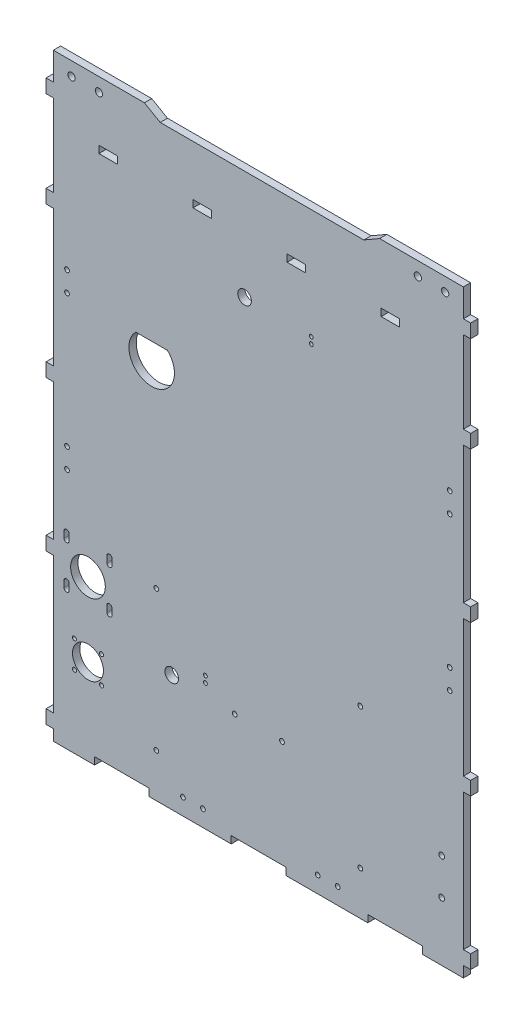
SolidWorks part; units mm, degrees
material "PMMA"
ref_plane "Plan de face" through (0, 0, 0) normal (0, 0, 1) x (1, 0, 0)
ref_plane "Plan de dessus" through (0, 0, 0) normal (0, 1, 0) x (1, 0, 0)
ref_plane "Plan de droite" through (0, 0, 0) normal (1, 0, 0) x (0, 0, -1)
sketch "Esquisse2" plane through (0, 0, -12) normal (0, 0, 1) x (1, 0, 0)
  line L1 (458.3, -56) -> (0, -56)
  line L2 (458.3, -56) -> (458.3, 601.3433)
  line L3 (458.3, 601.3433) -> (0, 601.3433)
  line L4 (-8, -44) -> (-8, -29)
  line L5 (-8, 121) -> (-8, 136)
  line L6 (458.3, -65.2452) -> (450.3, -65.2452) construction
  line L7 (450.3, -21) -> (450.3, -15.3297) construction
  line L8 (-8, 601.3433) -> (0, 601.3433) construction
  line L9 (-8, 286) -> (-8, 301)
  line L10 (0, -56) -> (0, -44)
  line L11 (0, 194.5096) -> (0, 601.3433) construction
  line L12 (0, -44) -> (-8, -44)
  line L13 (-8, -44) -> (-8, -29)
  line L14 (-8, -29) -> (0, -29)
  line L15 (0, -29) -> (0, 121)
  line L16 (0, 121) -> (-8, 121)
  line L17 (-8, 121) -> (-8, 136)
  line L18 (-8, 136) -> (0, 136)
  line L19 (0, 136) -> (0, 286)
  line L20 (0, 286) -> (-8, 286)
  line L21 (-8, 286) -> (-8, 301)
  line L22 (-8, 301) -> (0, 301)
  line L23 (0, 301) -> (0, 451)
  line L24 (0, 451) -> (-8, 451)
  line L25 (-8, 451) -> (-8, 466)
  line L26 (-8, 466) -> (0, 466)
  line L27 (0, 466) -> (0, 556)
  line L28 (0, 556) -> (-8, 556)
  line L29 (-8, 556) -> (-8, 571)
  line L30 (-8, 571) -> (0, 571)
  line L32 (-8, 451) -> (-8, 466)
  line L34 (-8, 556) -> (-8, 571)
  line L35 (0, 571) -> (0, 601.3433)
  arc A0 (55, 38.5) -> (21, 38.5) centre (38, 38.5) ccw construction
  arc A1 (21, 38.5) -> (55, 38.5) centre (38, 38.5) ccw construction
  arc A2 (25.4008, 53.3492) -> (20.9008, 53.3492) centre (23.1508, 53.3492) ccw construction
  arc A3 (20.9008, 53.3492) -> (25.4008, 53.3492) centre (23.1508, 53.3492) ccw construction
  arc A4 (25.4008, 23.6508) -> (20.9008, 23.6508) centre (23.1508, 23.6508) ccw construction
  arc A5 (20.9008, 23.6508) -> (25.4008, 23.6508) centre (23.1508, 23.6508) ccw construction
  arc A6 (55.0992, 53.3492) -> (50.5992, 53.3492) centre (52.8492, 53.3492) ccw construction
  arc A7 (50.5992, 53.3492) -> (55.0992, 53.3492) centre (52.8492, 53.3492) ccw construction
  arc A8 (55.0992, 23.6508) -> (50.5992, 23.6508) centre (52.8492, 23.6508) ccw construction
  arc A9 (50.5992, 23.6508) -> (55.0992, 23.6508) centre (52.8492, 23.6508) ccw construction
  arc A10 (55, 38.5) -> (21, 38.5) centre (38, 38.5) ccw
  arc A11 (21, 38.5) -> (55, 38.5) centre (38, 38.5) ccw
  arc A12 (25.4008, 53.3492) -> (20.9008, 53.3492) centre (23.1508, 53.3492) ccw
  arc A13 (20.9008, 53.3492) -> (25.4008, 53.3492) centre (23.1508, 53.3492) ccw
  arc A14 (25.4008, 23.6508) -> (20.9008, 23.6508) centre (23.1508, 23.6508) ccw
  arc A15 (20.9008, 23.6508) -> (25.4008, 23.6508) centre (23.1508, 23.6508) ccw
  arc A16 (55.0992, 53.3492) -> (50.5992, 53.3492) centre (52.8492, 53.3492) ccw
  arc A17 (50.5992, 53.3492) -> (55.0992, 53.3492) centre (52.8492, 53.3492) ccw
  arc A18 (55.0992, 23.6508) -> (50.5992, 23.6508) centre (52.8492, 23.6508) ccw
  arc A19 (50.5992, 23.6508) -> (55.0992, 23.6508) centre (52.8492, 23.6508) ccw
  point P68 (-4, 556)
  dimension "D1" = 8
  dimension "D2" = 15
  dimension "D3" = 15
  dimension "D4" = 15
  dimension "D5" = 15
  dimension "D6" = 15
  dimension "D7" = 9.2452
  dimension "D8" = 12
  dimension "D9" = 150
  dimension "D10" = 150
  dimension "D11" = 150
  dimension "D12" = 90
  dimension "D13" = 8
extrude "Boss.-Extru.1" add sketch "Esquisse2" along normal blind 8
sketch "Esquisse3" plane through (0, 0, -4) normal (0, 0, 1) x (1, 0, 0)
  line L0 (458.3, 528) -> (0, 528) construction
  line L1 (458.3, -56) -> (458.3, 601.3433) construction
  line L2 (0, 194.5096) -> (0, 601.3433) construction
  line L3 (458.3, 601.3433) -> (0, 601.3433) construction
  line L4 (0, 536) -> (458.3, 536) construction
  line L5 (153.3333, 528) -> (173.6333, 528)
  line L6 (50, 536) -> (70.3, 536)
  line L7 (50, 536) -> (50, 528)
  line L8 (50, 528) -> (70.3, 528)
  line L9 (70.3, 536) -> (70.3, 528)
  line L10 (153.3333, 536) -> (173.6333, 536)
  line L11 (173.6333, 536) -> (173.6333, 528)
  line L12 (153.3333, 536) -> (153.3333, 528)
  line L13 (256.6667, 528) -> (276.9667, 528)
  line L14 (256.6667, 536) -> (276.9667, 536)
  line L15 (276.9667, 536) -> (276.9667, 528)
  line L16 (256.6667, 536) -> (256.6667, 528)
  line L17 (360, 528) -> (380.3, 528)
  line L18 (360, 536) -> (380.3, 536)
  line L19 (380.3, 536) -> (380.3, 528)
  line L20 (360, 536) -> (360, 528)
  dimension "D1" = 8
  dimension "D2" = 20.3
  dimension "D3" = 50
  dimension "D5" = 65.3433
  dimension "D6" = 78
  dimension "D4" = 4
extrude "Enlèv. mat.-Extru.1" cut sketch "Esquisse3" against normal blind 8
sketch "Esquisse4" plane through (0, 0, -4) normal (0, 0, 1) x (1, 0, 0)
  line L0 (229.15, 640.3) -> (229.15, -56) construction
  line L1 (358.3, 601.3433) -> (340.9795, 591.3433)
  line L2 (340.9795, 591.3433) -> (117.3205, 591.3433)
  line L3 (458.3, -56) -> (458.3, 601.3433) construction
  line L4 (100, 601.3433) -> (117.3205, 591.3433)
  line L5 (0, 571) -> (0, 601.3433) construction
  line L24 (0, 601.3433) -> (0, 571)
  line L25 (0, 571) -> (-8, 571)
  line L26 (-8, 571) -> (-8, 556)
  line L27 (-8, 556) -> (0, 556)
  line L28 (0, 556) -> (0, 466)
  line L29 (0, 466) -> (-8, 466)
  line L30 (-8, 466) -> (-8, 451)
  line L31 (-8, 451) -> (0, 451)
  line L32 (0, 451) -> (0, 301)
  line L33 (0, 301) -> (-8, 301)
  line L34 (-8, 301) -> (-8, 286)
  line L35 (-8, 286) -> (0, 286)
  line L36 (0, 286) -> (0, 136)
  line L37 (0, 136) -> (-8, 136)
  line L38 (-8, 136) -> (-8, 121)
  line L39 (-8, 121) -> (0, 121)
  line L40 (0, 121) -> (0, -29)
  line L41 (0, -29) -> (-8, -29)
  line L42 (-8, -29) -> (-8, -44)
  line L43 (-8, -44) -> (0, -44)
  line L44 (0, -44) -> (0, -56)
  line L45 (0, -56) -> (458.3, -56)
  line L46 (458.3, -56) -> (458.3, 601.3433)
  line L47 (458.3, 601.3433) -> (0, 601.3433)
  line L69 (0, -56) -> (229.15, -56)
  line L71 (358.3, 601.3433) -> (100, 601.3433)
  point P14 (229.15, 591.3433)
  dimension "D2" = 30
  dimension "D3" = 20
  dimension "D4" = 100
  dimension "D5" = 100
  dimension "D1" = 0
extrude "Enlèv. mat.-Extru.2" cut sketch "Esquisse4" against normal blind 10 contours L71 L4 L2 L1
sketch "Esquisse5" plane through (0, 0, -4) normal (0, 0, 1) x (1, 0, 0)
  line L1 (340.9795, 591.3433) -> (117.3205, 591.3433) construction
  line L2 (458.3, -56) -> (0, -56) construction
  line L4 (225.15, 591.3433) -> (225.15, -56) construction
  line L5 (450.3, -44) -> (450.3, -56)
  line L6 (458.3, -44) -> (450.3, -44)
  line L7 (458.3, -56) -> (450.3, -56)
  line L8 (450.3, -29) -> (458.3, -29)
  line L9 (450.3, 121) -> (450.3, -29)
  line L10 (458.3, 121) -> (450.3, 121)
  line L11 (229.15, -56) -> (0, -56)
  line L12 (450.3, 136) -> (458.3, 136)
  line L13 (450.3, 286) -> (450.3, 136)
  line L14 (458.3, 286) -> (450.3, 286)
  line L16 (450.3, 301) -> (458.3, 301)
  line L17 (450.3, 451) -> (450.3, 301)
  line L18 (458.3, 451) -> (450.3, 451)
  line L20 (450.3, 466) -> (458.3, 466)
  line L21 (450.3, 556) -> (450.3, 466)
  line L22 (458.3, 556) -> (450.3, 556)
  line L24 (450.3, 571) -> (458.3, 571)
  line L25 (450.3, 601.3433) -> (450.3, 571)
  line L26 (458.3, -56) -> (458.3, 601.3433) construction
  line L27 (458.3, 601.3433) -> (358.3, 601.3433) construction
  line L28 (458.3, 601.3433) -> (358.3, 601.3433)
  line L29 (358.3, 601.3433) -> (340.9795, 591.3433)
  line L30 (340.9795, 591.3433) -> (117.3205, 591.3433)
  line L31 (117.3205, 591.3433) -> (100, 601.3433)
  line L32 (100, 601.3433) -> (0, 601.3433)
  line L33 (0, 601.3433) -> (0, 571)
  line L34 (0, 571) -> (-8, 571)
  line L35 (-8, 571) -> (-8, 556)
  line L36 (-8, 556) -> (0, 556)
  line L37 (0, 556) -> (0, 466)
  line L38 (0, 466) -> (-8, 466)
  line L39 (-8, 466) -> (-8, 451)
  line L40 (-8, 451) -> (0, 451)
  line L41 (0, 451) -> (0, 301)
  line L42 (0, 301) -> (-8, 301)
  line L43 (-8, 301) -> (-8, 286)
  line L44 (-8, 286) -> (0, 286)
  line L45 (0, 286) -> (0, 136)
  line L46 (0, 136) -> (-8, 136)
  line L47 (-8, 136) -> (-8, 121)
  line L48 (-8, 121) -> (0, 121)
  line L49 (0, 121) -> (0, -29)
  line L50 (0, -29) -> (-8, -29)
  line L51 (-8, -29) -> (-8, -44)
  line L52 (-8, -44) -> (0, -44)
  line L53 (0, -44) -> (0, -56)
  line L54 (0, -56) -> (458.3, -56)
  line L55 (458.3, -56) -> (458.3, 601.3433)
  line L61 (0, 601.3433) -> (0, 571) construction
  line L62 (0, 571) -> (-8, 571) construction
  line L63 (-8, 571) -> (-8, 556) construction
  line L64 (-8, 556) -> (0, 556) construction
  line L65 (0, 556) -> (0, 466) construction
  line L66 (0, 466) -> (-8, 466) construction
  line L67 (-8, 466) -> (-8, 451) construction
  line L68 (-8, 451) -> (0, 451) construction
  line L69 (0, 451) -> (0, 301) construction
  line L70 (0, 301) -> (-8, 301) construction
  line L71 (-8, 301) -> (-8, 286) construction
  line L72 (-8, 286) -> (0, 286) construction
  line L73 (0, 286) -> (0, 136) construction
  line L74 (0, 136) -> (-8, 136) construction
  line L75 (-8, 136) -> (-8, 121) construction
  line L76 (-8, 121) -> (0, 121) construction
  line L77 (0, 121) -> (0, -29) construction
  line L78 (0, -29) -> (-8, -29) construction
  line L79 (-8, -29) -> (-8, -44) construction
  line L80 (-8, -44) -> (0, -44) construction
  line L81 (0, -44) -> (0, -56) construction
  line L82 (458.3, -56) -> (458.3, 601.3433)
  line L83 (458.3, 601.3433) -> (450.3, 601.3433)
  dimension "D2" = 225.15
  dimension "D1" = 0
extrude "Enlèv. mat.-Extru.3" cut sketch "Esquisse5" against normal blind 10 and the other way through all contours L8 L82 L10 L9 | L7 L82 L6 L5 | L12 L82 L14 L13 | L16 L82 L18 L17 | L20 L82 L22 L21 | L82 L83 L25 L24
sketch "Esquisse6" plane through (0, 0, -12) normal (0, 0, 1) x (1, 0, 0)
  line L4 (17, 53.8297) -> (17, 23.1703)
  line L5 (22.6703, 17.5) -> (53.3297, 17.5)
  line L6 (59, 23.1703) -> (59, 53.8297)
  line L7 (53.3297, 59.5) -> (22.6703, 59.5)
  line L8 (17, 53.8297) -> (17, 23.1703)
  line L9 (22.6703, 17.5) -> (53.3297, 17.5)
  line L10 (59, 23.1703) -> (59, 53.8297)
  line L11 (53.3297, 59.5) -> (22.6703, 59.5)
  arc A0 (55, 38.5) -> (21, 38.5) centre (38, 38.5) ccw construction
  arc A1 (21, 38.5) -> (55, 38.5) centre (38, 38.5) ccw construction
  arc A2 (25.4008, 53.3492) -> (20.9008, 53.3492) centre (23.1508, 53.3492) ccw construction
  arc A3 (20.9008, 53.3492) -> (25.4008, 53.3492) centre (23.1508, 53.3492) ccw construction
  arc A4 (22.6703, 59.5) -> (17, 53.8297) centre (38, 38.5) ccw
  arc A5 (17, 23.1703) -> (22.6703, 17.5) centre (38, 38.5) ccw
  arc A6 (53.3297, 17.5) -> (59, 23.1703) centre (38, 38.5) ccw
  arc A7 (59, 53.8297) -> (53.3297, 59.5) centre (38, 38.5) ccw
  arc A8 (22.6703, 59.5) -> (17, 53.8297) centre (38, 38.5) ccw
  arc A9 (17, 23.1703) -> (22.6703, 17.5) centre (38, 38.5) ccw
  arc A10 (53.3297, 17.5) -> (59, 23.1703) centre (38, 38.5) ccw
  arc A11 (59, 53.8297) -> (53.3297, 59.5) centre (38, 38.5) ccw
  arc A12 (50.5992, 53.3492) -> (55.0992, 53.3492) centre (52.8492, 53.3492) ccw construction
  arc A13 (55.0992, 53.3492) -> (50.5992, 53.3492) centre (52.8492, 53.3492) ccw construction
  arc A14 (55.0992, 23.6508) -> (50.5992, 23.6508) centre (52.8492, 23.6508) ccw construction
  arc A15 (50.5992, 23.6508) -> (55.0992, 23.6508) centre (52.8492, 23.6508) ccw construction
  arc A16 (25.4008, 23.6508) -> (20.9008, 23.6508) centre (23.1508, 23.6508) ccw construction
  arc A17 (20.9008, 23.6508) -> (25.4008, 23.6508) centre (23.1508, 23.6508) ccw construction
  arc A18 (55, 38.5) -> (21, 38.5) centre (38, 38.5) ccw
  arc A19 (21, 38.5) -> (55, 38.5) centre (38, 38.5) ccw
  arc A20 (25.4008, 53.3492) -> (20.9008, 53.3492) centre (23.1508, 53.3492) ccw
  arc A21 (20.9008, 53.3492) -> (25.4008, 53.3492) centre (23.1508, 53.3492) ccw
  arc A22 (50.5992, 53.3492) -> (55.0992, 53.3492) centre (52.8492, 53.3492) ccw
  arc A23 (55.0992, 53.3492) -> (50.5992, 53.3492) centre (52.8492, 53.3492) ccw
  arc A24 (55.0992, 23.6508) -> (50.5992, 23.6508) centre (52.8492, 23.6508) ccw
  arc A25 (50.5992, 23.6508) -> (55.0992, 23.6508) centre (52.8492, 23.6508) ccw
  arc A26 (25.4008, 23.6508) -> (20.9008, 23.6508) centre (23.1508, 23.6508) ccw
  arc A27 (20.9008, 23.6508) -> (25.4008, 23.6508) centre (23.1508, 23.6508) ccw
  dimension "D1" = 0
extrude "Boss.-Extru.2" add sketch "Esquisse6" along normal blind 8
sketch "Esquisse7" plane through (0, 0, -4) normal (0, 0, 1) x (1, 0, 0)
  line L0 (38, 38.5) -> (38, 119.5) construction
  circle A0 centre (38, 119.5) radius 19.05
  dimension "D2" = 38.1
  dimension "D1" = 81
extrude "Enlèv. mat.-Extru.4" cut sketch "Esquisse7" against normal blind 10
sketch "Esquisse8" plane through (0, 0, -4) normal (0, 0, 1) x (1, 0, 0)
  circle A0 centre (61.55, 143.05) radius 2.8 construction
  circle A1 centre (14.45, 143.05) radius 2.8 construction
  circle A2 centre (14.45, 95.95) radius 2.8 construction
  circle A3 centre (61.55, 95.95) radius 2.8 construction
  circle A4 centre (61.55, 143.05) radius 2.8
  circle A5 centre (14.45, 143.05) radius 2.8
  circle A6 centre (14.45, 95.95) radius 2.8
  circle A7 centre (61.55, 95.95) radius 2.8
extrude "Enlèv. mat.-Extru.5" cut sketch "Esquisse8" against normal blind 10
sketch "Esquisse9" plane through (0, 0, -4) normal (0, 0, 1) x (1, 0, 0)
  circle A0 centre (426.5, 48.5) radius 3.15 construction
  circle A1 centre (426.5, 8.5) radius 3.15 construction
  circle A2 centre (426.5, 48.5) radius 3.15
  circle A3 centre (426.5, 8.5) radius 3.15
extrude "Enlèv. mat.-Extru.6" cut sketch "Esquisse9" against normal blind 10
sketch "Esquisse10" plane through (0, 0, -4) normal (0, 0, 1) x (1, 0, 0)
  circle A0 centre (251.15, 69.5) radius 2.65 construction
  circle A1 centre (199.15, 69.5) radius 2.65 construction
  circle A2 centre (251.15, 69.5) radius 2.65
  circle A3 centre (199.15, 69.5) radius 2.65
extrude "Enlèv. mat.-Extru.7" cut sketch "Esquisse10" against normal blind 10
sketch "Esquisse12" plane through (0, 0, -12) normal (0, 0, -1) x (-1, 0, 0)
  line L0 (-450.3, -56) -> (0, -56) construction
  line L1 (-405.3, -56) -> (-345.3, -56)
  line L2 (-405.3, -56) -> (-405.3, -48)
  line L3 (-405.3, -48) -> (-345.3, -48)
  line L4 (-345.3, -56) -> (-345.3, -48)
  line L5 (-255.3, -56) -> (-195.3, -56)
  line L6 (-255.3, -56) -> (-255.3, -48)
  line L7 (-255.3, -48) -> (-195.3, -48)
  line L8 (-195.3, -56) -> (-195.3, -48)
  line L9 (-255.3, -48) -> (-255.3, -56) construction
  line L10 (-105.3, -56) -> (-45.3, -56)
  line L11 (-105.3, -56) -> (-105.3, -48)
  line L12 (-105.3, -48) -> (-45.3, -48)
  line L13 (-45.3, -56) -> (-45.3, -48)
  line L14 (-105.3, -48) -> (-105.3, -56) construction
  line L15 (-45.3, -56) -> (-105.3, -56) construction
  dimension "D1" = 60
  dimension "D2" = 60
  dimension "D3" = 60
  dimension "D4" = 8
  dimension "D5" = 8
  dimension "D6" = 8
extrude "Enlèv. mat.-Extru.8" cut sketch "Esquisse12" against normal blind 10
sketch "Esquisse13" plane through (0, 0, -4) normal (0, 0, 1) x (1, 0, 0)
  line L0 (314.8, -38) -> (309.8, -38) construction
  line L1 (292.8, -38) -> (287.8, -38) construction
  line L2 (166.8, -38) -> (161.8, -38) construction
  line L3 (144.8, -38) -> (139.8, -38) construction
  arc A0 (309.8, -35.5) -> (309.8, -40.5) centre (309.8, -38) ccw construction
  arc A1 (292.8, -40.5) -> (292.8, -35.5) centre (292.8, -38) ccw construction
  arc A2 (287.8, -35.5) -> (287.8, -40.5) centre (287.8, -38) ccw construction
  circle A3 centre (312.3, -38) radius 2.6
  circle A4 centre (290.3, -38) radius 2.6
  arc A5 (166.8, -40.5) -> (166.8, -35.5) centre (166.8, -38) ccw construction
  arc A6 (161.8, -35.5) -> (161.8, -40.5) centre (161.8, -38) ccw construction
  arc A7 (144.8, -40.5) -> (144.8, -35.5) centre (144.8, -38) ccw construction
  arc A8 (139.8, -35.5) -> (139.8, -40.5) centre (139.8, -38) ccw construction
  circle A9 centre (164.3, -38) radius 2.6
  circle A10 centre (142.3, -38) radius 2.6
  dimension "D1" = 5.2
  dimension "D2" = 5.2
  dimension "D3" = 5.2
  dimension "D4" = 5.2
extrude "Enlèv. mat.-Extru.9" cut sketch "Esquisse13" against normal blind 10
sketch "Esquisse15" plane through (0, 0, -12) normal (0, 0, -1) x (-1, 0, 0)
  line L0 (-432.6, 375.5) -> (-432.6, 380.5) construction
  line L1 (-438, 380.5) -> (-438, 375.5) construction
  line L2 (-432.6, 397.5) -> (-432.6, 402.5) construction
  line L3 (-438, 402.5) -> (-438, 397.5) construction
  line L4 (-432.6, 375.5) -> (-432.6, 380.5) construction
  line L5 (-438, 380.5) -> (-438, 375.5) construction
  line L6 (-432.6, 397.5) -> (-432.6, 402.5) construction
  line L7 (-438, 402.5) -> (-438, 397.5) construction
  line L8 (-17.7, 380.5) -> (-17.7, 375.5) construction
  line L9 (-17.7, 380.5) -> (-17.7, 375.5) construction
  line L10 (-12.3, 397.5) -> (-12.3, 402.5) construction
  line L11 (-17.7, 402.5) -> (-17.7, 397.5) construction
  line L12 (-12.3, 375.5) -> (-12.3, 380.5) construction
  line L13 (-12.3, 397.5) -> (-12.3, 402.5) construction
  line L14 (-17.7, 402.5) -> (-17.7, 397.5) construction
  line L15 (-12.3, 375.5) -> (-12.3, 380.5) construction
  line L16 (-435.3, 402.5) -> (-435.3, 397.5) construction
  line L17 (-435.3, 380.5) -> (-435.3, 375.5) construction
  line L18 (-15, 402.5) -> (-15, 397.5) construction
  line L19 (-15, 380.5) -> (-15, 375.5) construction
  arc A0 (-438, 375.5) -> (-432.6, 375.5) centre (-435.3, 375.5) ccw construction
  arc A1 (-432.6, 380.5) -> (-438, 380.5) centre (-435.3, 380.5) ccw construction
  arc A2 (-438, 397.5) -> (-432.6, 397.5) centre (-435.3, 397.5) ccw construction
  arc A3 (-432.6, 402.5) -> (-438, 402.5) centre (-435.3, 402.5) ccw construction
  arc A4 (-438, 375.5) -> (-432.6, 375.5) centre (-435.3, 375.5) ccw construction
  arc A5 (-432.6, 380.5) -> (-438, 380.5) centre (-435.3, 380.5) ccw construction
  arc A6 (-438, 397.5) -> (-432.6, 397.5) centre (-435.3, 397.5) ccw construction
  arc A7 (-432.6, 402.5) -> (-438, 402.5) centre (-435.3, 402.5) ccw construction
  arc A8 (-12.3, 402.5) -> (-17.7, 402.5) centre (-15, 402.5) ccw construction
  arc A9 (-17.7, 397.5) -> (-12.3, 397.5) centre (-15, 397.5) ccw construction
  arc A10 (-12.3, 380.5) -> (-17.7, 380.5) centre (-15, 380.5) ccw construction
  arc A11 (-17.7, 375.5) -> (-12.3, 375.5) centre (-15, 375.5) ccw construction
  arc A12 (-12.3, 402.5) -> (-17.7, 402.5) centre (-15, 402.5) ccw construction
  arc A13 (-17.7, 397.5) -> (-12.3, 397.5) centre (-15, 397.5) ccw construction
  arc A14 (-12.3, 380.5) -> (-17.7, 380.5) centre (-15, 380.5) ccw construction
  arc A15 (-17.7, 375.5) -> (-12.3, 375.5) centre (-15, 375.5) ccw construction
  circle A16 centre (-435.3, 378) radius 2.6
  circle A17 centre (-435.3, 400) radius 2.6
  circle A18 centre (-15, 378) radius 2.6
  circle A19 centre (-15, 400) radius 2.6
  dimension "D1" = 5.2
  dimension "D2" = 5.2
  dimension "D3" = 5.2
  dimension "D4" = 5.2
extrude "Enlèv. mat.-Extru.10" cut sketch "Esquisse15" against normal blind 10
sketch "Esquisse16" plane through (0, 0, -4) normal (0, 0, 1) x (1, 0, 0)
  circle A0 centre (337.15, 146) radius 2.6 construction
  circle A1 centre (113.15, 146) radius 2.6 construction
  circle A2 centre (113.15, -8) radius 2.6 construction
  circle A3 centre (337.15, -8) radius 2.6 construction
  circle A4 centre (337.15, 146) radius 2.6
  circle A5 centre (113.15, 146) radius 2.6
  circle A6 centre (113.15, -8) radius 2.6
  circle A7 centre (337.15, -8) radius 2.6
extrude "Enlèv. mat.-Extru.11" cut sketch "Esquisse16" against normal blind 10
sketch "Esquisse17" plane through (0, 0, -4) normal (0, 0, 1) x (1, 0, 0)
  circle A0 centre (20, 586.3433) radius 4 construction
  circle A1 centre (50, 586.3433) radius 4 construction
  circle A2 centre (400.3, 586.3433) radius 4 construction
  circle A3 centre (430.3, 586.3433) radius 4 construction
  circle A4 centre (20, 586.3433) radius 4
  circle A5 centre (50, 586.3433) radius 4
  circle A6 centre (400.3, 586.3433) radius 4
  circle A7 centre (430.3, 586.3433) radius 4
extrude "Enlèv. mat.-Extru.12" cut sketch "Esquisse17" against normal blind 10
sketch "Esquisse18" plane through (0, 0, -12) normal (0, 0, -1) x (-1, 0, 0)
  circle A0 centre (-167, 90) radius 2.1 construction
  circle A1 centre (-167, 83) radius 2.1 construction
  circle A2 centre (-167, 90) radius 2.1
  circle A3 centre (-167, 83) radius 2.1
  circle A4 centre (-283.3, 470.5) radius 2.1 construction
  circle A5 centre (-283.3, 463.5) radius 2.1 construction
  circle A6 centre (-283.3, 470.5) radius 2.1
  circle A7 centre (-283.3, 463.5) radius 2.1
extrude "Enlèv. mat.-Extru.13" cut sketch "Esquisse18" against normal blind 10
sketch "Esquisse19" plane through (0, 0, -4) normal (0, 0, 1) x (1, 0, 0)
  line L0 (14.45, 143.05) -> (14.45, 150.05) construction
  line L1 (11.65, 143.05) -> (11.65, 150.05)
  line L2 (17.25, 143.05) -> (17.25, 150.05)
  line L3 (61.55, 143.05) -> (61.55, 150.05) construction
  line L4 (58.75, 143.05) -> (58.75, 150.05)
  line L5 (64.35, 143.05) -> (64.35, 150.05)
  line L6 (61.55, 95.95) -> (61.55, 102.95) construction
  line L7 (58.75, 95.95) -> (58.75, 102.95)
  line L8 (64.35, 95.95) -> (64.35, 102.95)
  line L9 (14.45, 95.95) -> (14.45, 102.95) construction
  line L10 (11.65, 95.95) -> (11.65, 102.95)
  line L11 (17.25, 95.95) -> (17.25, 102.95)
  arc A0 (11.65, 143.05) -> (17.25, 143.05) centre (14.45, 143.05) ccw
  arc A1 (17.25, 150.05) -> (11.65, 150.05) centre (14.45, 150.05) ccw
  arc A2 (58.75, 143.05) -> (64.35, 143.05) centre (61.55, 143.05) ccw
  arc A3 (64.35, 150.05) -> (58.75, 150.05) centre (61.55, 150.05) ccw
  arc A4 (58.75, 95.95) -> (64.35, 95.95) centre (61.55, 95.95) ccw
  arc A5 (64.35, 102.95) -> (58.75, 102.95) centre (61.55, 102.95) ccw
  arc A6 (11.65, 95.95) -> (17.25, 95.95) centre (14.45, 95.95) ccw
  arc A7 (17.25, 102.95) -> (11.65, 102.95) centre (14.45, 102.95) ccw
  point P3 (14.45, 146.55)
  point P8 (61.55, 146.55)
  point P16 (61.55, 99.45)
  point P24 (14.45, 99.45)
  dimension "D1" = 2.8
  dimension "D2" = 2.8
  dimension "D3" = 2.8
  dimension "D4" = 2.8
  dimension "D5" = 7
  dimension "D6" = 7
  dimension "D7" = 7
  dimension "D8" = 7
extrude "Enlèv. mat.-Extru.14" cut sketch "Esquisse19" against normal blind 10
sketch "Esquisse20" plane through (0, 0, -4) normal (0, 0, 1) x (1, 0, 0)
  circle A0 centre (108, 360.5) radius 25
  dimension "D1" = 50
extrude "Enlèv. mat.-Extru.15" cut sketch "Esquisse20" against normal blind 10
sketch "Esquisse21" plane through (0, 0, -12) normal (0, 0, -1) x (-1, 0, 0)
  line L0 (-90.6506, 378.5) -> (-125.3494, 378.5)
  line L1 (-125.3494, 378.5) -> (-90.6506, 378.5) construction
  circle A0 centre (-108, 360.5) radius 25 construction
  arc A1 (-90.6506, 378.5) -> (-125.3494, 378.5) centre (-108, 360.5) ccw
extrude "Boss.-Extru.3" add sketch "Esquisse21" against normal blind 8
sketch "Esquisse22" plane through (0, 0, -12) normal (0, 0, -1) x (-1, 0, 0)
  line L0 (0, 466) -> (0, 556) construction
  line L1 (-340.9795, 591.3433) -> (-117.3205, 591.3433) construction
  line L2 (0, -29) -> (0, 121) construction
  line L3 (-45.3, -48) -> (-105.3, -48) construction
  circle A0 centre (-210, 471.3433) radius 7.5
  circle A1 centre (-130, 72) radius 7.5
  dimension "D1" = 210
  dimension "D2" = 15
  dimension "D3" = 120
  dimension "D4" = 15
  dimension "D5" = 130
  dimension "D6" = 120
extrude "Enlèv. mat.-Extru.16" cut sketch "Esquisse22" against normal blind 10
sketch "Esquisse23" plane through (0, 0, -12) normal (0, 0, -1) x (-1, 0, 0)
  line L0 (-420.8294, 232) -> (-450.3, 232) construction
  line L1 (-458.3, 286) -> (-450.3, 286) construction
  line L2 (-450.3, 286) -> (-450.3, 136) construction
  line L3 (-420.8294, 210) -> (-445.4085, 210) construction
  line L4 (-435.3, 378) -> (-435.3, -56) construction
  line L5 (-450.3, -56) -> (-405.3, -56) construction
  line L6 (-15, 378) -> (-15, 177.7691) construction
  line L7 (0, 232) -> (-29.5535, 232) construction
  line L8 (0, 136) -> (0, 286) construction
  line L9 (0, 286) -> (8, 286) construction
  circle A0 centre (-435.3, 232) radius 2.6
  circle A1 centre (-435.3, 210) radius 2.6
  circle A3 centre (-15, 232) radius 2.6
  circle A4 centre (-15, 210) radius 2.6
  dimension "D3" = 5.2
  dimension "D4" = 5.2
  dimension "D6" = 22
  dimension "D7" = 5.2
  dimension "D8" = 5.2
  dimension "D1" = 54
  dimension "D2" = 22
  dimension "D5" = 54
extrude "Enlèv. mat.-Extru.17" cut sketch "Esquisse23" against normal blind 10
